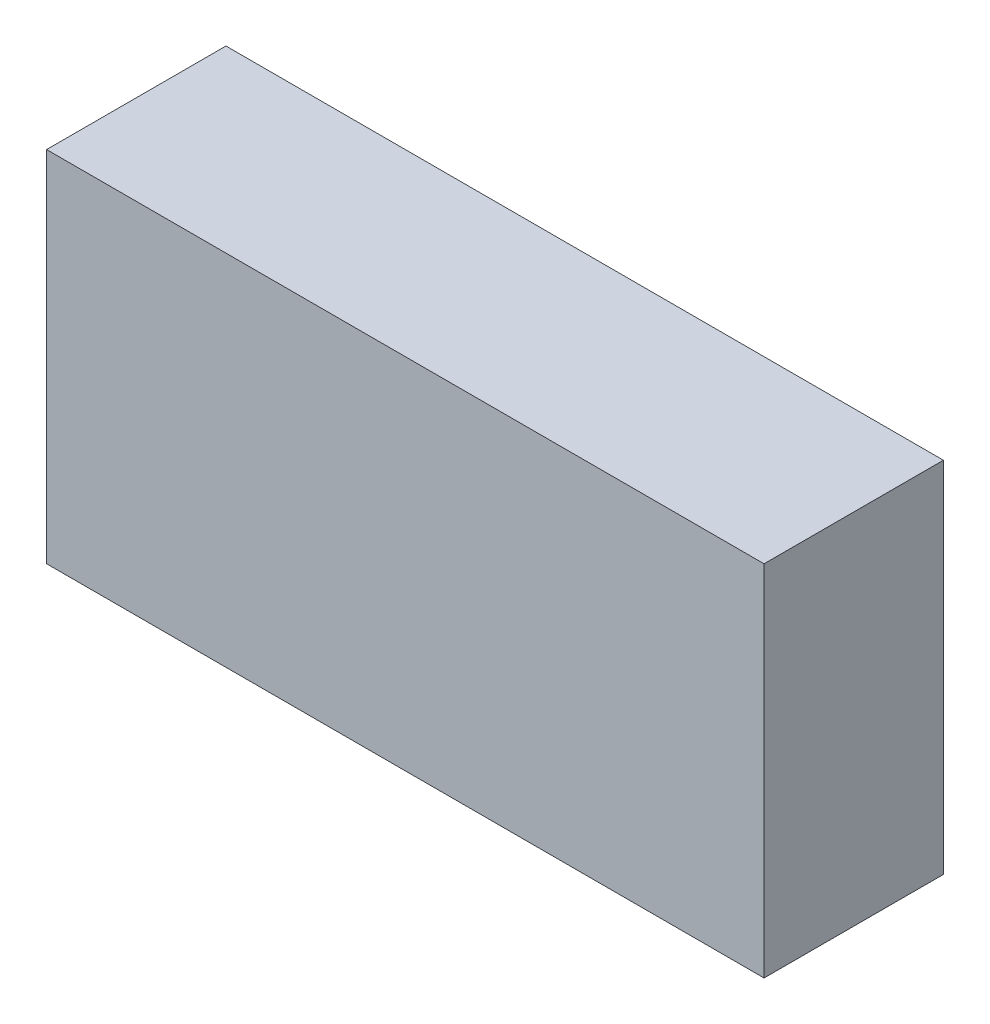
SolidWorks part; units mm, degrees
ref_plane "Front Plane" through (0, 0, 0) normal (0, 0, 1) x (1, 0, 0)
ref_plane "Top Plane" through (0, 0, 0) normal (0, 1, 0) x (1, 0, 0)
ref_plane "Right Plane" through (0, 0, 0) normal (1, 0, 0) x (0, 0, -1)
sketch "Sketch1" plane through (0, 0, 0) normal (0, 0, 1) x (1, 0, 0)
  line L1 (-66.5623, 44.3919) -> (35.0377, 44.3919)
  line L2 (-66.5623, 44.3919) -> (-66.5623, -6.4081)
  line L3 (-66.5623, -6.4081) -> (35.0377, -6.4081)
  line L4 (35.0377, 44.3919) -> (35.0377, -6.4081)
  dimension "D1" = 101.6
  dimension "2" = 50.8
extrude "Boss-Extrude1" add sketch "Sketch1" along normal blind 25.4 contours L1 L4 L3 L2
